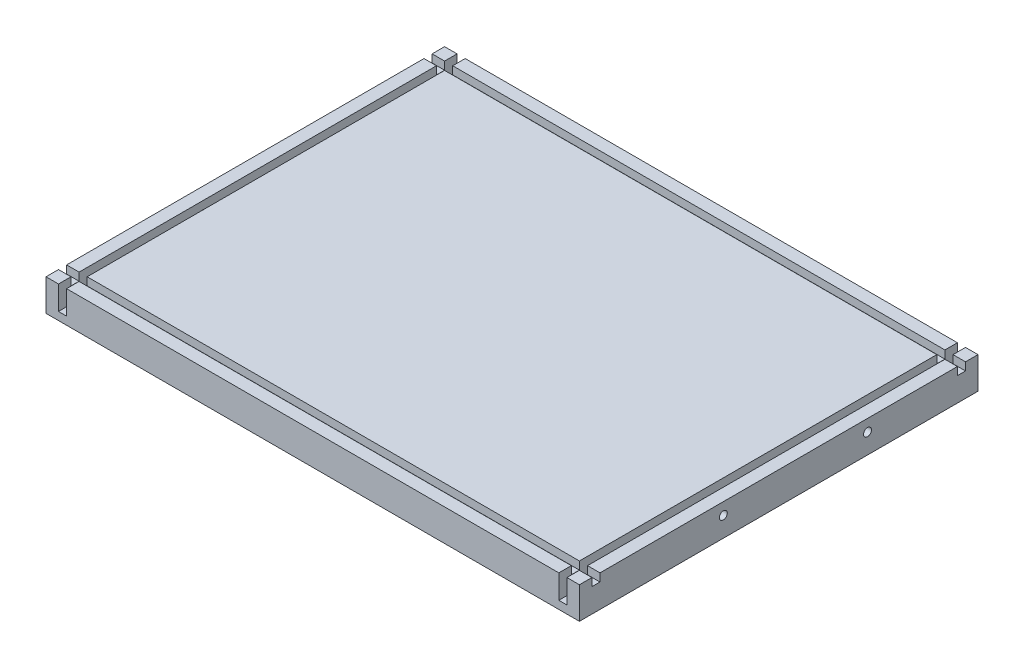
SolidWorks part; units mm, degrees
ref_plane "Front Plane" through (0, 0, 0) normal (0, 0, 1) x (1, 0, 0)
ref_plane "Top Plane" through (0, 0, 0) normal (0, 1, 0) x (1, 0, 0)
ref_plane "Right Plane" through (0, 0, 0) normal (1, 0, 0) x (0, 0, -1)
sketch "Sketch1" plane through (0, 0, 0) normal (0, 1, 0) x (1, 0, 0)
  line L1 (0, 0) -> (427.3, 0)
  line L2 (0, 0) -> (0, 319.3)
  line L3 (0, 319.3) -> (427.3, 319.3)
  line L4 (427.3, 0) -> (427.3, 319.3)
  dimension "D1" = 427.3
  dimension "D2" = 319.3
extrude "Boss-Extrude1" add sketch "Sketch1" along normal blind 25.4
sketch "Sketch2" plane through (0, 25.4, 0) normal (0, 1, 0) x (1, 0, 0)
  line L8 (410.8, 302.8) -> (410.8, 16.5)
  line L14 (16.5, 16.5) -> (16.5, 302.8)
  line L16 (10, 16.5) -> (10, 302.8)
  line L17 (417.3, 16.5) -> (417.3, 302.8)
  line L18 (0, 319.3) -> (0, 0) construction
  line L19 (0, 0) -> (427.3, 0) construction
  line L20 (427.3, 319.3) -> (0, 319.3) construction
  line L22 (16.5, 309.3) -> (16.5, 319.3)
  line L24 (10, 309.3) -> (10, 319.3)
  line L31 (410.8, 309.3) -> (410.8, 319.3)
  line L33 (417.3, 309.3) -> (417.3, 319.3)
  line L40 (410.8, 10) -> (410.8, 0)
  line L42 (417.3, 10) -> (417.3, 0)
  line L52 (16.5, 10) -> (16.5, 0)
  line L54 (10, 10) -> (10, 0)
  line L55 (10, 0) -> (16.5, 0)
  line L56 (410.8, 0) -> (417.3, 0)
  line L58 (410.8, 319.3) -> (417.3, 319.3)
  line L61 (10, 319.3) -> (16.5, 319.3)
  line L62 (410.8, 309.3) -> (410.8, 302.8)
  line L63 (417.3, 309.3) -> (417.3, 302.8)
  line L64 (417.3, 16.5) -> (417.3, 10)
  line L65 (410.8, 16.5) -> (410.8, 10)
  line L66 (16.5, 16.5) -> (16.5, 10)
  line L67 (10, 16.5) -> (10, 10)
  line L68 (16.5, 309.3) -> (16.5, 302.8)
  line L69 (10, 309.3) -> (10, 302.8)
  dimension "D1" = 407.3
  dimension "D2" = 10
  dimension "D3" = 299.3
  dimension "D5" = 6.5
  dimension "D6" = 6.5
  dimension "D14" = 407.3
extrude "Cut-Extrude1" cut sketch "Sketch2" against normal blind 19.05
sketch "Sketch6" plane through (0, 25.4, 0) normal (0, 1, 0) x (1, 0, 0)
  line L0 (0, 319.3) -> (0, 0) construction
  line L1 (0, 16.5) -> (427.3, 16.5)
  line L2 (0, 16.5) -> (0, 10)
  line L3 (0, 10) -> (427.3, 10)
  line L4 (427.3, 16.5) -> (427.3, 10)
  line L5 (427.3, 0) -> (427.3, 319.3) construction
  line L6 (16.5, 0) -> (410.8, 0) construction
  line L7 (0, 302.8) -> (427.3, 302.8)
  line L8 (0, 302.8) -> (0, 309.3)
  line L9 (0, 309.3) -> (427.3, 309.3)
  line L10 (427.3, 302.8) -> (427.3, 309.3)
  line L11 (410.8, 319.3) -> (16.5, 319.3) construction
  dimension "D1" = 6.5
  dimension "D2" = 10
  dimension "D3" = 10
  dimension "D4" = 6.5
extrude "Cut-Extrude4" cut sketch "Sketch6" against normal blind 6.35
sketch "Sketch4" plane through (427.3, 0, 0) normal (1, 0, 0) x (0, 0, -1)
  line L0 (16.5, 19.05) -> (16.5, 25.4) construction
  line L1 (0, 25.4) -> (10, 25.4) construction
  circle A0 centre (115.275, 15.875) radius 3.175
  circle A1 centre (230.775, 15.875) radius 3.175
  dimension "D1" = 9.525
  dimension "D2" = 9.525
  dimension "D3" = 98.775
  dimension "D4" = 214.275
  dimension "D5" = 6.35
extrude "Cut-Extrude2" cut sketch "Sketch4" against normal blind 38.1
sketch "Sketch5" plane through (0, 0, 0) normal (-1, 0, 0) x (0, 0, 1)
  line L0 (-319.3, 25.4) -> (-309.3, 25.4) construction
  line L2 (-16.5, 19.05) -> (-16.5, 25.4) construction
  circle A0 centre (-230.775, 15.875) radius 3.175
  circle A1 centre (-115.275, 15.875) radius 3.175
  dimension "D1" = 9.525
  dimension "D2" = 9.525
  dimension "D3" = 6.35
  dimension "D4" = 214.275
  dimension "D5" = 98.775
extrude "Cut-Extrude3" cut sketch "Sketch5" against normal blind 38.1
